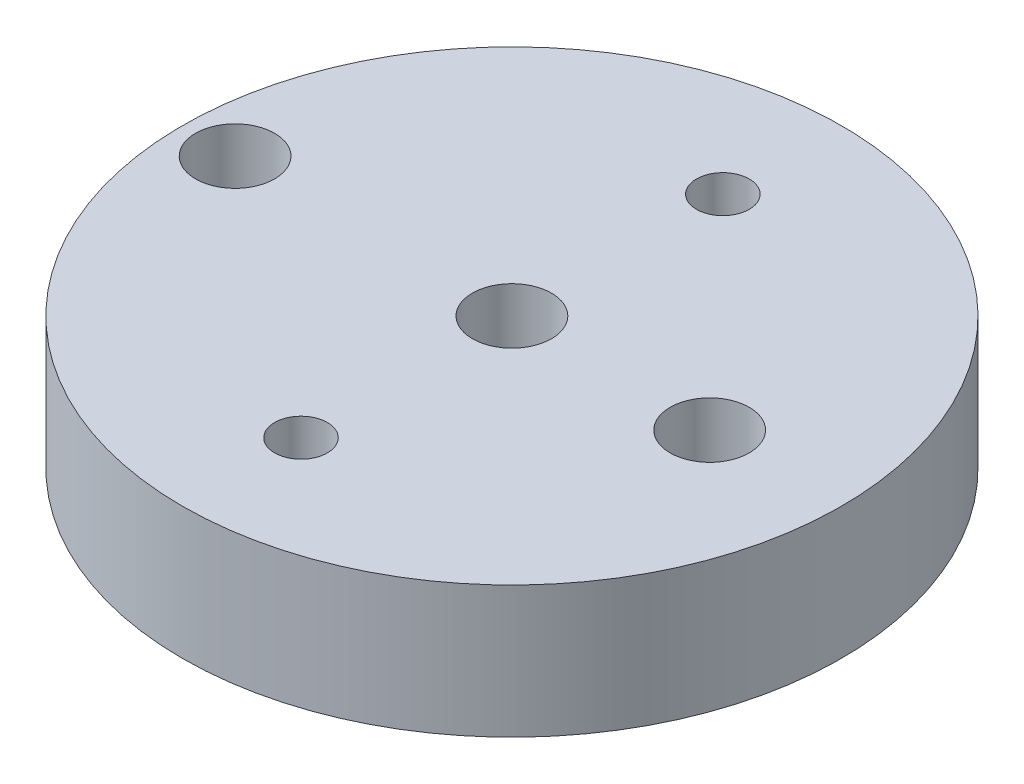
SolidWorks part; units mm, degrees
ref_plane "Front Plane" through (0, 0, 0) normal (0, 0, 1) x (1, 0, 0)
ref_plane "Top Plane" through (0, 0, 0) normal (0, 1, 0) x (1, 0, 0)
ref_plane "Right Plane" through (0, 0, 0) normal (1, 0, 0) x (0, 0, -1)
sketch "Sketch1" plane through (0, 0, 0) normal (0, 1, 0) x (1, 0, 0)
  line L0 (0, 0) -> (0, -8) construction
  circle A0 centre (0, 0) radius 12.5
  circle A1 centre (0, -8) radius 1
  circle A2 centre (-8, 0) radius 1 construction
  circle A3 centre (0, 8) radius 1
  circle A4 centre (8, 0) radius 1 construction
  circle A5 centre (0, 0) radius 1.5
  circle A6 centre (-10.5, 0) radius 1.5
  circle A7 centre (7.5, 0) radius 1.5
  circle A8 centre (0, 0) radius 5.75 construction
  dimension "D1" = 25
  dimension "D2" = 2
  dimension "D3" = 3
  dimension "D6" = 3
  dimension "D7" = 3
  dimension "D9" = 10.5
  dimension "D10" = 11.5
  dimension "D5" = 8
  dimension "D8" = 18
  dimension "D4" = 4
extrude "Boss-Extrude1" add sketch "Sketch1" along normal blind 5
